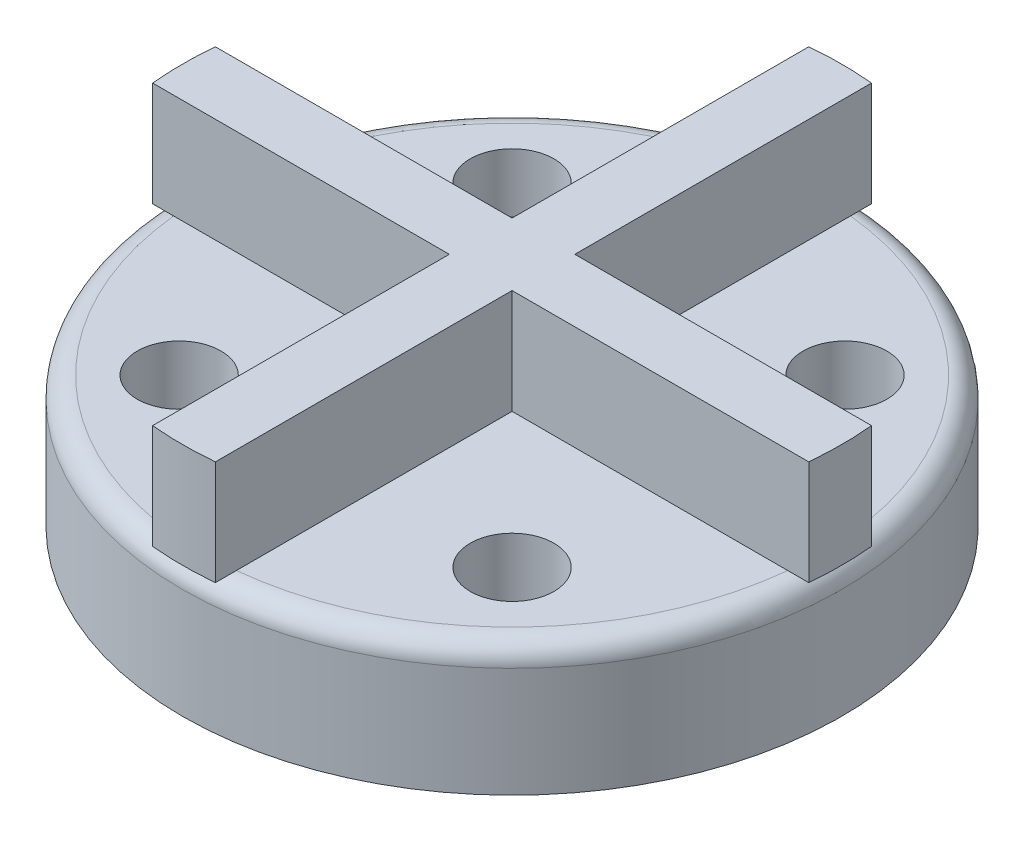
SolidWorks part; units mm, degrees
ref_plane "前视基准面" through (0, 0, 0) normal (0, 0, 1) x (1, 0, 0)
ref_plane "上视基准面" through (0, 0, 0) normal (0, 1, 0) x (1, 0, 0)
ref_plane "右视基准面" through (0, 0, 0) normal (1, 0, 0) x (0, 0, -1)
sketch "草图1" plane through (0, 0, 0) normal (0, 1, 0) x (1, 0, 0)
  line L0 (-31.5, 0) -> (31.5, 0) construction
  line L1 (-15.9099, 15.9099) -> (0, 0) construction
  circle A0 centre (0, 0) radius 22.5 construction
  circle A1 centre (0, 0) radius 31.5
  circle A2 centre (-15.9099, 15.9099) radius 4
  circle A3 centre (15.9099, 15.9099) radius 4
  circle A4 centre (15.9099, -15.9099) radius 4
  circle A5 centre (-15.9099, -15.9099) radius 4
  dimension "D1" = 45
  dimension "D2" = 63
  dimension "D3" = 8
  dimension "D4" = 45
  dimension "D5" = 4
extrude "凸台-拉伸1" add sketch "草图1" along normal blind 12.5
fillet "圆角1" radius 2 1 edges at (0, 12.5, 31.5)
sketch "草图2" plane through (0, 12.5, 0) normal (0, 1, 0) x (1, 0, 0)
  line L0 (3, 31.3568) -> (3, 3)
  line L1 (-31.3568, -3) -> (-3, -3)
  line L3 (-31.3568, 3) -> (-3, 3)
  line L7 (-3, 31.3568) -> (-3, 3)
  line L8 (-3, -3) -> (-3, -31.3568)
  line L9 (3, 3) -> (31.3568, 3)
  line L11 (3, -3) -> (3, -31.3568)
  line L12 (3, -3) -> (31.3568, -3)
  circle A0 centre (0, 0) radius 31.5 construction
  arc A1 (-31.3568, 3) -> (-31.3568, -3) centre (0, 0) ccw
  arc A2 (31.3568, -3) -> (31.3568, 3) centre (0, 0) ccw
  arc A3 (-3, -31.3568) -> (3, -31.3568) centre (0, 0) ccw
  arc A4 (3, 31.3568) -> (-3, 31.3568) centre (0, 0) ccw
  point P0 (0, 0)
  dimension "D1" = 6
  dimension "D2" = 2
extrude "凸台-拉伸2" add sketch "草图2" along normal blind 10
